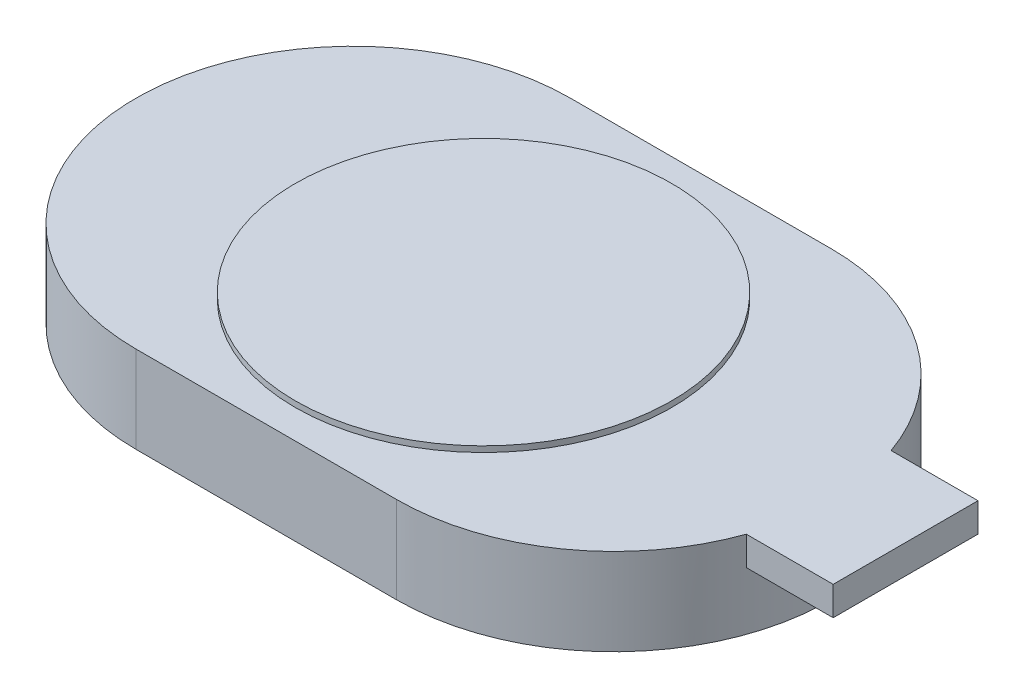
SolidWorks part; units mm, degrees
ref_plane "前视基准面" through (0, 0, 0) normal (0, 0, 1) x (1, 0, 0)
ref_plane "上视基准面" through (0, 0, 0) normal (0, 1, 0) x (1, 0, 0)
ref_plane "右视基准面" through (0, 0, 0) normal (1, 0, 0) x (0, 0, -1)
other "Configuration Table"
sketch "草图1" plane through (0, 0, 0) normal (0, 1, 0) x (1, 0, 0)
  line L0 (-4.5, 0) -> (4.5, 0) construction
  line L1 (-4.5, 7.5) -> (4.5, 7.5)
  line L2 (-4.5, -7.5) -> (4.5, -7.5)
  arc A0 (-4.5, 7.5) -> (-4.5, -7.5) centre (-4.5, 0) ccw
  arc A1 (4.5, -7.5) -> (4.5, 7.5) centre (4.5, 0) ccw
  point P2 (0, 0)
  point P8 (-12, 0)
  point P9 (12, 0)
  dimension "D1" = 15
  dimension "D2" = 24
extrude "凸台-拉伸1" add sketch "草图1" along normal blind 3
sketch "草图2" plane through (0, 3, 0) normal (0, 1, 0) x (1, 0, 0)
  circle A0 centre (0, 0) radius 6.5
  dimension "D1" = 13
extrude "凸台-拉伸2" add sketch "草图2" along normal blind 0.2
sketch "草图4" plane through (0, 3, 0) normal (0, 1, 0) x (1, 0, 0)
  line L0 (0, 0) -> (12, 0) construction
  line L2 (14.5711, 2.5) -> (11.5711, 2.5)
  line L3 (14.5711, 2.5) -> (14.5711, -2.5)
  line L4 (14.5711, -2.5) -> (11.5711, -2.5)
  line L5 (11.5711, 2.5) -> (11.5711, -2.5)
  arc A0 (4.5, -7.5) -> (4.5, 7.5) centre (4.5, 0) ccw construction
  point P10 (0, 0)
  dimension "D1" = 5
  dimension "D2" = 3
extrude "凸台-拉伸3" add sketch "草图4" against normal blind 1
